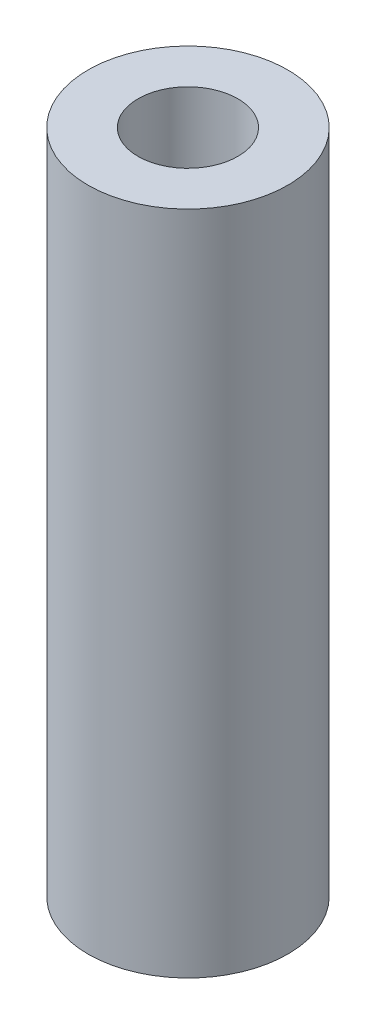
SolidWorks part; units mm, degrees
ref_plane "Front Plane" through (0, 0, 0) normal (0, 0, 1) x (1, 0, 0)
ref_plane "Top Plane" through (0, 0, 0) normal (0, 1, 0) x (1, 0, 0)
ref_plane "Right Plane" through (0, 0, 0) normal (1, 0, 0) x (0, 0, -1)
sketch "Szkic1" plane through (0, 0, 0) normal (0, 1, 0) x (1, 0, 0)
  circle A0 centre (0, 0) radius 1.5
  circle A1 centre (0, 0) radius 3
  dimension "D1" = 3
  dimension "D2" = 6
extrude "Dodanie-wyciągnięcie1" add sketch "Szkic1" along normal blind 20
